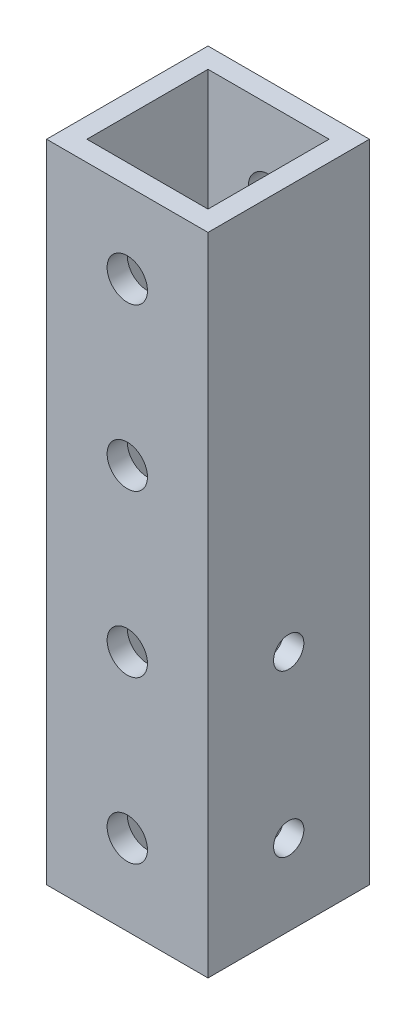
SolidWorks part; units mm, degrees
material "6063-T1"
ref_plane "Front Plane" through (0, 0, 0) normal (0, 0, 1) x (1, 0, 0)
ref_plane "Top Plane" through (0, 0, 0) normal (0, 1, 0) x (1, 0, 0)
ref_plane "Right Plane" through (0, 0, 0) normal (1, 0, 0) x (0, 0, -1)
sketch "Sketch1" plane through (0, 0, 0) normal (0, 0, 1) x (1, 0, 0)
  line L1 (0, 0) -> (25.4, 0)
  line L2 (0, 0) -> (0, 101.6)
  line L3 (0, 101.6) -> (25.4, 101.6)
  line L4 (25.4, 0) -> (25.4, 101.6)
  dimension "D1" = 25.4
  dimension "D2" = 101.6
extrude "Boss-Extrude1" add sketch "Sketch1" along normal blind 25.4
shell "Shell1" thickness 3.175
sketch "Sketch2" plane through (0, 0, 25.4) normal (0, 0, 1) x (1, 0, 0)
  line L0 (0, 0) -> (25.4, 0) construction
  line L1 (25.4, 0) -> (25.4, 101.6) construction
  line L2 (25.4, 101.6) -> (0, 101.6) construction
  circle A0 centre (12.7, 12.7) radius 3.175
  circle A1 centre (12.7, 38.1) radius 3.175
  circle A2 centre (12.7, 88.9) radius 3.175
  circle A3 centre (12.7, 63.5) radius 3.175
  dimension "D1" = 12.7
  dimension "D4" = 6.35
  dimension "D5" = 6.35
  dimension "D8" = 6.35
  dimension "D9" = 6.35
  dimension "D2" = 25.4
  dimension "D3" = 12.7
  dimension "D6" = 12.7
  dimension "D7" = 25.4
extrude "Cut-Extrude1" cut sketch "Sketch2" against normal through all
sketch "Sketch3" plane through (25.4, 0, 0) normal (1, 0, 0) x (0, 0, -1)
  line L0 (-25.4, 0) -> (0, 0) construction
  line L1 (0, 0) -> (0, 101.6) construction
  circle A0 centre (-12.7, 12.7) radius 2.3813
  circle A1 centre (-12.7, 38.1) radius 2.3812
  dimension "D3" = 4.7625
  dimension "D4" = 4.7625
  dimension "D1" = 38.1
  dimension "D2" = 12.7
  dimension "D5" = 12.7
extrude "Cut-Extrude2" cut sketch "Sketch3" against normal blind 7.62
